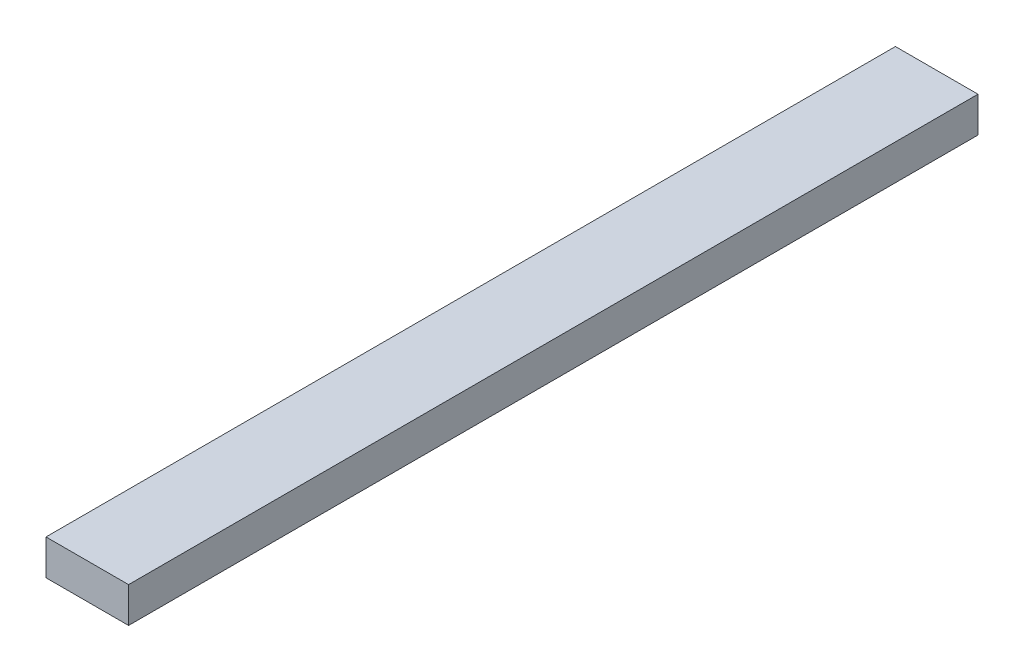
SolidWorks part; units mm, degrees
material "Pine"
ref_plane "Front Plane" through (0, 0, 0) normal (0, 0, 1) x (1, 0, 0)
ref_plane "Top Plane" through (0, 0, 0) normal (0, 1, 0) x (1, 0, 0)
ref_plane "Right Plane" through (0, 0, 0) normal (1, 0, 0) x (0, 0, -1)
sketch "Sketch1" plane through (0, 0, 0) normal (0, 0, 1) x (1, 0, 0)
  line L1 (-914.4, 0) -> (-825.5, 0)
  line L2 (-914.4, 0) -> (-914.4, -38.1)
  line L3 (-914.4, -38.1) -> (-825.5, -38.1)
  line L4 (-825.5, 0) -> (-825.5, -38.1)
  dimension "D1" = 88.9
  dimension "D2" = 38.1
extrude "Boss-Extrude1" add sketch "Sketch1" against normal up to surface (914.4 mm away)
